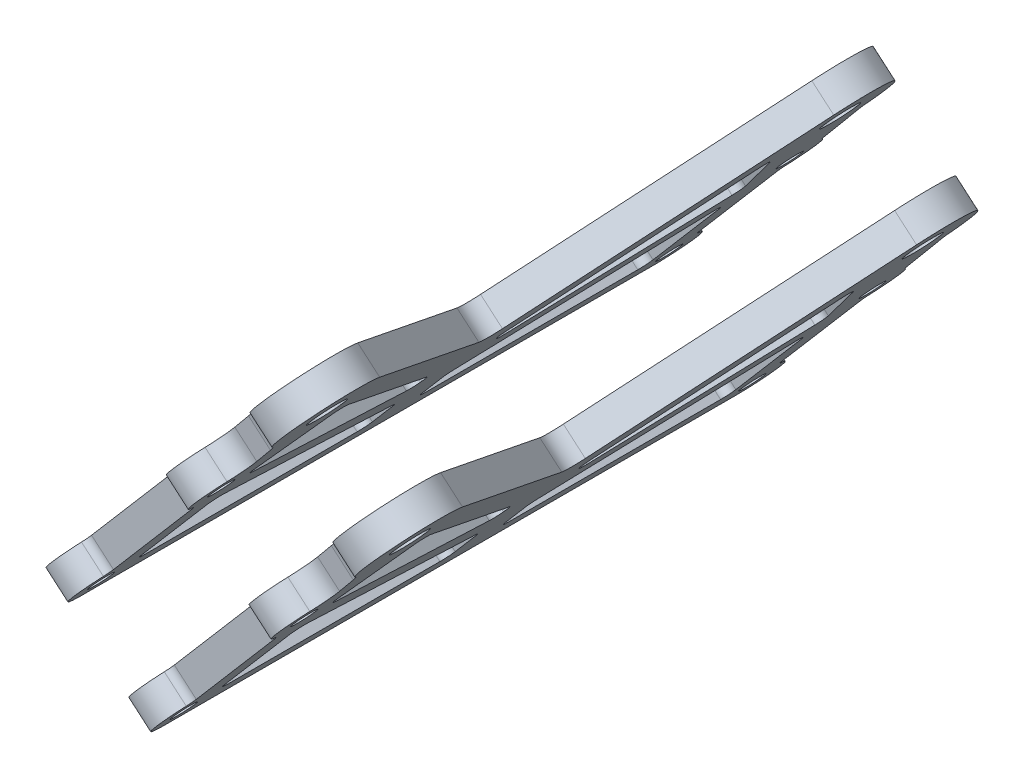
SolidWorks part; units mm, degrees
material "7075-T6, Plate (SS)"
ref_plane "Ground Plane" through (0, 0, 0) normal (0, 0, 1) x (1, 0, 0)
ref_plane "Side Plane" through (0, 0, 0) normal (0, 1, 0) x (1, 0, 0)
ref_plane "Rear Axle Centerline" through (0, 0, 0) normal (1, 0, 0) x (0, 0, -1)
sketch "Chassis Side View" plane through (0, 0, 0) normal (0, 1, 0) x (1, 0, 0)
  line L0 (0, -381) -> (2300, -381) construction
  line L1 (1150, -381) -> (1150, -856.742)
  line L2 (2150, -381) -> (2150, -1062.9307) construction
  line L3 (-753.0356, 0) -> (753.0356, 0) construction
  line L4 (2450, -381) -> (2450, -1062.9307) construction
  dimension "D1" = 2300
  dimension "D2" = 475.742
  dimension "D3" = 1150
  dimension "D4" = 381
  dimension "D5" = 150
  dimension "D6" = 150
ref_plane "Front Axle Centerline" through (2300, 0, 0) normal (1, 0, 0) x (0, 0, -1)
sketch "Front Wheel Assy Constraints" plane through (2300, 0, 0) normal (1, 0, 0) x (0, 0, -1)
  line L0 (0, 727.5) -> (0, 822.5)
  line L1 (0, 822.5) -> (-271.78, 822.5)
  line L2 (-271.78, 822.5) -> (-551.18, 822.5)
  line L3 (-551.18, 822.5) -> (-551.18, 727.5)
  line L4 (-551.18, 775) -> (0, 775) construction
  line L5 (-271.78, 822.5) -> (-271.78, 775) construction
  line L6 (-551.18, 727.5) -> (-445.4516, 727.5)
  line L7 (-445.4516, 727.5) -> (-445.4516, 798.5)
  line L8 (-445.4516, 798.5) -> (-105.7284, 798.5)
  line L9 (-105.7284, 798.5) -> (-105.7284, 727.5)
  line L10 (-105.7284, 727.5) -> (0, 727.5)
  line L11 (0, 0) -> (-673.9047, 0) construction
  line L13 (0, 753.0356) -> (0, -753.0356) construction
  dimension "D1" = 95
  dimension "D2" = 279.4
  dimension "D3" = 271.78
  dimension "D4" = 23.5
  dimension "D5" = 1550
sketch "Front Sus Front View" plane through (2300, 0, 0) normal (1, 0, 0) x (0, 0, -1)
  line L0 (0, 775) -> (0, 768.65) construction
  line L1 (0, 753.0356) -> (0, -753.0356) construction
  line L2 (0, 768.65) -> (-762, 634.2888) construction
  line L3 (0, 768.65) -> (-745.3671, 768.65) construction
  line L4 (-366.7919, -1090.2477) -> (-525.9451, 520.8571) construction
  line L5 (-366.7919, -1090.2477) -> (-379.5678, 520.8571) construction
  line L6 (-366.7919, -1090.2477) -> (0, 775) construction
  line L7 (-525.9451, 520.8571) -> (-541, 673.2571)
  line L8 (-379.5678, 520.8571) -> (-381, 701.4694)
  line L9 (0, 0) -> (-152.4, 0) construction
  line L13 (-525.9451, 520.8571) -> (-379.5678, 520.8571) construction
  dimension "D1" = 6.35
  dimension "D2" = 10
  dimension "D3" = 152.4
  dimension "D4" = 1865.2477
  dimension "D6" = 381
  dimension "D7" = 541
  dimension "D8" = 153.1418
  dimension "D5" = 152.4
ref_plane "Fron Wheel Side View Plane" through (0, 775, 0) normal (0, 1, 0) x (1, 0, 0)
sketch "Front SVSA" plane through (0, 775, 0) normal (0, 1, 0) x (1, 0, 0)
  line L0 (2271.684, -676.7175) -> (2328.316, 133.1575)
  line L1 (2300, 0) -> (2300, -771.0839) construction
  line L2 (2300, 0) -> (-2450.054, -116.0888) construction
  line L3 (-2450.054, -116.0888) -> (2298.2335, -297.0415) construction
  line L4 (-753.0356, 0) -> (753.0356, 0) construction
  point P5 (2300, -271.78)
  dimension "D1" = 4
  dimension "D2" = 1.4
  dimension "D3" = 4750.054
sketch3d "Front Chassis Side Axes"
  line L0 (2300, 520.8571, 379.5678) -> (2300, 701.4694, 381) construction
  line L1 (2300, 520.8571, 525.9451) -> (2300, 673.2571, 541) construction
  line L2 (2300, 520.8571, 379.5678) -> (2300, 701.4694, 381) construction
  line L3 (2300, 520.8571, 525.9451) -> (2300, 673.2571, 541) construction
  line L4 (2300, 673.2571, 541) -> (2300, 775, 551.0507) construction
  line L5 (2300, 701.4694, 381) -> (2300, 775, 381.5831) construction
  line L6 (2300, 775, 0) -> (2300, 775, 771.0839) construction
  line L7 (-2450.054, 775, 116.0888) -> (2349.7917, 775, 555.6101) construction
  line L8 (-2450.054, 775, 116.0888) -> (2349.9221, 775, 384.3734) construction
  line L9 (2349.9221, 775, 384.3734) -> (2177.377, 520.8571, 372.714) construction
  line L10 (2349.7917, 775, 555.6101) -> (2225.4174, 520.8571, 519.1156) construction
  line L11 (2300, 520.8571, 525.9451) -> (2300, 520.8571, 519.1156) construction
  line L12 (2300, 520.8571, 519.1156) -> (2225.4174, 520.8571, 519.1156) construction
  line L13 (2598.7501, 520.8571, 553.3017) -> (1702.4998, 520.8571, 471.2321)
  line L14 (2300, 520.8571, 379.5678) -> (2300, 520.8571, 372.714) construction
  line L15 (2300, 520.8571, 372.714) -> (2177.377, 520.8571, 372.714) construction
  line L16 (2599.5325, 520.8571, 396.3095) -> (1700.935, 520.8571, 346.0843)
  dimension "D1" = 50
  dimension "D2" = 50
  dimension "D3" = 600
  dimension "D4" = 300
  dimension "D5" = 600
  dimension "D6" = 300
sketch3d "Front Left Control Arm"
  line L0 (2300, 520.8571, 379.5678) -> (2300, 701.4694, 381) construction
  line L2 (2300, 520.8571, 379.5678) -> (2300, 701.4694, 381) construction
  line L3 (2300, 520.8571, 525.9451) -> (2300, 673.2571, 541) construction
  line L4 (2598.7501, 520.8571, 553.3017) -> (1702.4998, 520.8571, 471.2321) construction
  line L5 (2599.5325, 520.8571, 396.3095) -> (1700.935, 520.8571, 346.0843) construction
  line L6 (2598.7501, 520.8571, 553.3017) -> (1702.4998, 520.8571, 471.2321) construction
  line L7 (2599.5325, 520.8571, 396.3095) -> (1700.935, 520.8571, 346.0843) construction
  line L8 (2450, 520.8571, 539.6806) -> (2280.5957, 673.2571, 539.2232)
  line L9 (2280.5957, 673.2571, 539.2232) -> (2150, 520.8571, 512.2097)
  line L10 (2300, 520.8571, 525.9451) -> (2300, 673.2571, 541) construction
  line L11 (2300, 673.2571, 541) -> (2280.5957, 673.2571, 539.2232) construction
  line L12 (2271.684, 775, 676.7175) -> (2328.316, 775, -133.1575) construction
  line L13 (2150, 0, 512.2097) -> (2150, 520.8571, 512.2097) construction
  line L14 (2292.3517, 701.4694, 380.5725) -> (2292.3517, 775, 381.1556) construction
  line L15 (2150, 0, 381) -> (2150, 0, 1062.9307) construction
  line L16 (2450, 0, 539.6806) -> (2450, 520.8571, 539.6806) construction
  line L17 (2450, 0, 381) -> (2450, 0, 1062.9307) construction
  line L18 (2450, 520.8571, 387.9517) -> (2292.3517, 701.4694, 380.5725)
  line L19 (2292.3517, 701.4694, 380.5725) -> (2150, 520.8571, 371.1838)
  line L20 (2300, 701.4694, 381) -> (2292.3517, 701.4694, 380.5725) construction
  line L21 (2450, 0, 387.9517) -> (2450, 520.8571, 387.9517) construction
  line L22 (2150, 0, 371.1838) -> (2150, 520.8571, 371.1838) construction
  line L23 (2280.5957, 673.2571, 539.2232) -> (2280.5957, 775, 549.2738) construction
sketch3d "Front Control Arm"
  line L0 (2450, 520.8571, 387.9517) -> (2292.3517, 701.4694, 380.5725) construction
  line L1 (2292.3517, 701.4694, 380.5725) -> (2150, 520.8571, 371.1838) construction
  line L2 (2280.5957, 673.2571, 539.2232) -> (2150, 520.8571, 512.2097) construction
  line L3 (2450, 520.8571, 539.6806) -> (2280.5957, 673.2571, 539.2232) construction
  line L4 (2450, 520.8571, 387.9517) -> (2292.3517, 701.4694, 380.5725)
  line L5 (2292.3517, 701.4694, 380.5725) -> (2150, 520.8571, 371.1838)
  line L6 (2280.5957, 673.2571, 539.2232) -> (2150, 520.8571, 512.2097)
  line L7 (2450, 520.8571, 539.6806) -> (2280.5957, 673.2571, 539.2232)
  line L8 (2450, -520.8571, 539.6806) -> (2280.5957, -673.2571, 539.2232)
  line L9 (2280.5957, -673.2571, 539.2232) -> (2150, -520.8571, 512.2097)
  line L10 (2292.3517, -701.4694, 380.5725) -> (2150, -520.8571, 371.1838)
  line L11 (2450, -520.8571, 387.9517) -> (2292.3517, -701.4694, 380.5725)
ref_plane "Max Droop Plane" through (0, 0, -25.4) normal (0, 0, 1) x (1, 0, 0)
sketch3d "Shock"
  line L0 (2292.3517, 701.4694, 380.5725) -> (2293.5626, 664.4705, 414.2387) construction
  line L1 (2300, 520.8571, 525.9451) -> (2298.2629, 520.8571, 544.9158) construction
  line L2 (2150, 520.8571, 512.2097) -> (2450, 520.8571, 539.6806) construction
  line L3 (2300, 520.8571, 525.9451) -> (2300, 230.5152, 525.9451) construction
  line L4 (2293.5626, 664.4705, 414.2387) -> (2298.2629, 520.8571, 544.9158)
  dimension "D1" = 50.038
  dimension "D2" = 19.05
sketch3d "Parametric Analysis"
  line L2 (2300, 822.5, 0) -> (2300, 822.5, 271.78) construction
  line L3 (2300.4137, 822.5, 271.7939) -> (2300.4137, 822.5, -88.8537) construction
  line L4 (2450, 520.8571, 387.9517) -> (2292.3526, 701.4695, 380.5568)
  line L5 (2292.3526, 701.4695, 380.5568) -> (2150, 520.8571, 371.1838)
  line L6 (2450, 520.8571, 539.6806) -> (2280.5972, 673.2586, 539.2077)
  line L7 (2280.5972, 673.2586, 539.2077) -> (2150, 520.8571, 512.2097)
  line L8 (2292.3517, 701.4694, 380.5725) -> (2300, 822.5, 271.78) construction
  line L9 (2450, 520.8571, 387.9517) -> (2292.3517, 701.4694, 380.5725) construction
  line L10 (2292.3517, 701.4694, 380.5725) -> (2150, 520.8571, 371.1838) construction
  line L11 (2450, 520.8571, 539.6806) -> (2280.5957, 673.2571, 539.2232) construction
  line L12 (2280.5957, 673.2571, 539.2232) -> (2150, 520.8571, 512.2097) construction
  line L13 (2280.5957, 673.2571, 539.2232) -> (2292.3517, 701.4694, 380.5725) construction
  line L14 (2300, 822.5, 271.78) -> (2280.5957, 673.2571, 539.2232) construction
  line L15 (2300, 822.5, 271.78) -> (2300.4132, 720.8156, 271.78) construction
  line L16 (2280.5972, 673.2586, 539.2077) -> (2300.4137, 822.5, 271.7939) construction
  line L17 (2300.4137, 822.5, 271.7939) -> (2292.3526, 701.4695, 380.5568) construction
  line L18 (2280.5972, 673.2586, 539.2077) -> (2292.3526, 701.4695, 380.5568) construction
  line L19 (2300.4137, 822.5, 271.7939) -> (2300.4137, 720.8148, 271.7641) construction
  line L23 (2292.3517, 701.4694, 380.5725) -> (2265.8007, 667.7821, 378.8214) construction
  line L30 (2265.8007, 667.7821, 378.8214) -> (2325.2406, 663.7898, 382.112) construction
  line L31 (2325.2406, 663.7898, 382.112) -> (2293.5626, 664.4705, 414.2387) construction
  line L32 (2292.3517, 701.4694, 380.5725) -> (2325.2406, 663.7898, 382.112) construction
  line L33 (2293.5626, 664.4705, 414.2387) -> (2265.8007, 667.7821, 378.8214) construction
  line L34 (2292.3526, 701.4695, 380.5568) -> (2293.5633, 664.4722, 414.2247) construction
  line L35 (2292.3517, 701.4694, 380.5725) -> (2293.5626, 664.4705, 414.2387) construction
  line L39 (2300.4137, 822.5, 271.7939) -> (2300.4137, 822.5798, 0.014)
  line L40 (2300.4137, 822.5798, 0.014) -> (2300.4137, 727.5798, -0.014)
  line L41 (2300, 727.5, 0) -> (2300, 822.5, 0) construction
  line L42 (2298.2629, 520.8571, 544.9158) -> (2293.5633, 664.4722, 414.2247)
  point P5 (2300.4137, 775.0798, 0)
  dimension "D1" = 25.4
  dimension "D2" = 194.2357
  dimension "D3" = 0.0798
  dimension "D4" = 0.017
sketch3d "3DSketch1"
  line L0 (2293.5626, 664.4705, 414.2387) -> (2298.2629, 520.8571, 544.9158) construction
  line L1 (2280.5972, 673.2586, 539.2077) -> (2150, 520.8571, 512.2097) construction
  line L2 (2450, 520.8571, 539.6806) -> (2280.5972, 673.2586, 539.2077) construction
  line L3 (2292.3526, 701.4695, 380.5568) -> (2150, 520.8571, 371.1838) construction
  line L4 (2450, 520.8571, 387.9517) -> (2292.3526, 701.4695, 380.5568) construction
  line L5 (2293.5626, 664.4705, 414.2387) -> (2298.2629, 520.8571, 544.9158)
  line L6 (2280.5972, 673.2586, 539.2077) -> (2150, 520.8571, 512.2097)
  line L7 (2450, 520.8571, 539.6806) -> (2280.5972, 673.2586, 539.2077)
  line L8 (2292.3526, 701.4695, 380.5568) -> (2150, 520.8571, 371.1838)
  line L9 (2450, 520.8571, 387.9517) -> (2292.3526, 701.4695, 380.5568)
  line L10 (2450, 520.8571, 539.6806) -> (2450, 470.0571, 539.6806) construction
  line L11 (2150, 520.8571, 512.2097) -> (2150, 470.0571, 512.2097) construction
  line L12 (2298.2629, 520.8571, 544.9158) -> (2298.2629, 470.0571, 544.9158) construction
  line L13 (2450, 520.8571, 387.9517) -> (2450, 470.0571, 387.9517) construction
  line L14 (2150, 520.8571, 371.1838) -> (2150, 470.0571, 371.1838) construction
  line L15 (2150, -520.8571, 512.2097) -> (2150, -470.0571, 512.2097) construction
  line L16 (2298.2629, -520.8571, 544.9158) -> (2298.2629, -470.0571, 544.9158) construction
  line L17 (2450, -520.8571, 539.6806) -> (2450, -470.0571, 539.6806) construction
  line L18 (2293.5626, -664.4705, 414.2387) -> (2298.2629, -520.8571, 544.9158)
  line L19 (2280.5972, -673.2586, 539.2077) -> (2150, -520.8571, 512.2097)
  line L20 (2450, -520.8571, 539.6806) -> (2280.5972, -673.2586, 539.2077)
  line L21 (2450, -520.8571, 387.9517) -> (2450, -470.0571, 387.9517) construction
  line L22 (2150, -520.8571, 371.1838) -> (2150, -470.0571, 371.1838) construction
  line L23 (2292.3526, -701.4695, 380.5568) -> (2150, -520.8571, 371.1838)
  line L24 (2450, -520.8571, 387.9517) -> (2292.3526, -701.4695, 380.5568)
  line L25 (2280.5972, 673.2586, 539.2077) -> (2280.5972, 673.2586, 216.3834) construction
  line L26 (2450, 520.8571, 539.6806) -> (2457.3728, 529.0523, 539.6794) construction
  line L27 (2300, 775, 551.18) -> (2300, 775, 0) construction
  line L29 (2457.3728, 529.0523, 539.6794) -> (2420.3829, 562.3299, 539.5762) construction
  dimension "D1" = 50.8
  dimension "D2" = 304.9478
  dimension "D3" = 544.9185
  dimension "D4" = 11.0236
ref_plane "Plane1" through (0, 718.612, 0) normal (0, 1, 0) x (1, 0, 0)
ref_plane "Plane2" through (982.32, -841.7776, 0) normal (-0.7593, 0.6507, 0) x (-0.6449, -0.7526, -0.1333)
sketch "Sketch1" plane through (982.32, -841.7776, 0) normal (-0.7593, 0.6507, 0) x (-0.6449, -0.7526, -0.1333)
  line L0 (-1846.7729, 268.4004) -> (-1827.9718, 128.6334) construction
  line L1 (-1846.7729, 268.4004) -> (-1849.6512, 289.7977) construction
  line L2 (-1837.3723, 198.5169) -> (-1809.8881, 202.214) construction
  line L3 (-1846.7729, 268.4004) -> (-1808.5429, 273.543) construction
  line L4 (-1825.0935, 107.2362) -> (-1849.3765, 125.8105)
  line L5 (-1849.6512, 289.7977) -> (-1868.1701, 265.5221)
  line L6 (-1849.6512, 289.7977) -> (-1748.9581, 303.3427)
  line L7 (-1825.0935, 107.2362) -> (-1724.4004, 120.7811)
  line L8 (-1827.9718, 128.6334) -> (-1825.0935, 107.2362) construction
  line L9 (-1748.9581, 303.3427) -> (-1724.4004, 120.7811)
  line L10 (-1868.1701, 265.5221) -> (-1849.3765, 125.8105)
  line L11 (-1764.717, 287.127) -> (-1815.0635, 280.3545) construction
  circle A0 centre (-1846.7729, 268.4004) radius 4.7625
  circle A1 centre (-1827.9718, 128.6334) radius 4.7625
  circle A2 centre (-1764.717, 287.127) radius 3.175
  circle A4 centre (-1815.0635, 280.3545) radius 3.175
  circle A5 centre (-1743.8841, 132.256) radius 3.175
  circle A6 centre (-1794.2307, 125.4835) radius 3.175
  circle A7 centre (-1779.4738, 206.3053) radius 3.175
  point P6 (-1837.3723, 198.5169)
  dimension "D1" = 9.525
  dimension "D2" = 9.525
  dimension "D11" = 6.35
  dimension "D15" = 6.35
  dimension "D16" = 6.35
  dimension "D3" = 21.59
  dimension "D4" = 21.59
  dimension "D5" = 21.59
  dimension "D6" = 101.6
  dimension "D7" = 101.6
  dimension "D8" = 21.59
  dimension "D9" = 140.97
  dimension "D10" = 30.5329
  dimension "D12" = 13.97
  dimension "D13" = 17.78
  dimension "D14" = 50.8
  dimension "D17" = 43.18
  dimension "D18" = 92.1029
extrude "Boss-Extrude1" add sketch "Sketch1" along normal blind 18.9611 and the other way blind 18.9611
ref_plane "Cutting Plane" through (967.9221, -829.4397, 0) normal (-0.7593, 0.6507, 0) x (0, 0, 1)
sketch "Sketch4" plane through (967.9221, -829.4397, 0) normal (-0.7593, 0.6507, 0) x (0, 0, 1)
  line L0 (512.2097, 1794.5055) -> (441.6967, 1736.0855) construction
  line L1 (441.6967, 1736.0855) -> (519.8297, 1710.6855) construction
  line L2 (519.8297, 1761.4855) -> (441.6967, 1736.0855) construction
  line L3 (441.6967, 1736.0855) -> (363.5638, 1761.4855) construction
  line L4 (441.6967, 1736.0855) -> (363.5638, 1710.6855) construction
  line L6 (363.5638, 1761.4855) -> (371.1838, 1794.5055) construction
  line L7 (519.8297, 1761.4855) -> (522.1855, 1754.2388) construction
  line L8 (522.1855, 1752.5829) -> (522.1855, 1719.5881)
  line L9 (512.2097, 1794.5055) -> (519.8297, 1761.4855) construction
  line L10 (512.2097, 1794.5055) -> (520.3121, 1784.7259) construction
  line L12 (361.208, 1752.5829) -> (361.208, 1719.5881)
  line L13 (363.5638, 1703.0655) -> (519.8297, 1703.0655)
  line L15 (363.5638, 1761.4855) -> (361.208, 1754.2388) construction
  line L16 (520.0113, 1782.5593) -> (518.9924, 1775.2208)
  line L20 (371.1838, 1794.5055) -> (441.6967, 1736.0855) construction
  line L21 (371.1838, 1794.5055) -> (379.2863, 1804.2851) construction
  line L23 (441.6967, 1769.1055) -> (441.6967, 1703.0655) construction
  line L28 (379.2863, 1804.2851) -> (438.4558, 1755.2631)
  line L30 (504.1072, 1804.2851) -> (444.9377, 1755.2631)
  line L36 (381.7632, 1781.226) -> (375.0049, 1760.437)
  line L37 (376.6352, 1757.2362) -> (428.2621, 1740.4529)
  line L38 (431.0033, 1741.248) -> (431.1991, 1741.4843)
  line L39 (430.8636, 1745.0608) -> (385.7992, 1782.3967)
  line L40 (503.5863, 1782.8465) -> (510.634, 1761.167)
  line L41 (509.0037, 1757.9661) -> (455.2625, 1740.4956)
  line L42 (452.202, 1741.782) -> (452.0386, 1742.1112)
  line L43 (452.6934, 1745.1963) -> (499.5502, 1784.0171)
  line L44 (533.7997, 1794.5055) -> (512.2097, 1816.0955)
  line L45 (512.2097, 1816.0955) -> (371.2397, 1816.0954)
  line L46 (371.2397, 1816.0954) -> (349.5938, 1794.5055)
  line L47 (349.5938, 1794.5055) -> (349.5938, 1692.9055)
  line L48 (349.5938, 1692.9055) -> (533.7997, 1692.9055)
  line L49 (533.7997, 1692.9055) -> (533.7997, 1794.5055)
  line L50 (360.5084, 1786.6541) -> (358.7544, 1768.2714)
  line L51 (379.2863, 1804.2851) -> (360.1806, 1788.1637) construction
  arc A0 (523.5016, 1754.8085) -> (522.8037, 1768.5012) centre (519.8297, 1761.4855) ccw
  arc A2 (521.6038, 1785.9592) -> (504.1072, 1804.2851) centre (512.2097, 1794.5055) ccw
  arc A4 (359.8919, 1754.8085) -> (358.0604, 1766.7559) centre (363.5638, 1761.4855) cw
  arc A5 (520.0113, 1782.5593) -> (521.6038, 1785.9592) centre (526.3009, 1781.6861) cw
  arc A6 (522.8037, 1768.5012) -> (518.9924, 1775.2208) centre (525.2821, 1774.3476) cw
  arc A7 (379.2863, 1804.2851) -> (360.1806, 1788.1637) centre (371.1838, 1794.5055) ccw
  arc A10 (428.2621, 1740.4529) -> (431.0033, 1741.248) centre (429.0474, 1742.8685) ccw
  arc A11 (431.1991, 1741.4843) -> (430.8636, 1745.0608) centre (429.2432, 1743.1048) ccw
  arc A12 (375.0049, 1760.437) -> (376.6352, 1757.2362) centre (377.4205, 1759.6517) ccw
  arc A13 (381.7632, 1781.226) -> (385.7992, 1782.3967) centre (384.1787, 1780.4407) cw
  arc A14 (452.6934, 1745.1963) -> (452.0386, 1742.1112) centre (454.3139, 1743.2403) ccw
  arc A15 (452.202, 1741.782) -> (455.2625, 1740.4956) centre (454.4773, 1742.9111) ccw
  arc A16 (509.0037, 1757.9661) -> (510.634, 1761.167) centre (508.2184, 1760.3817) ccw
  arc A17 (503.5863, 1782.8465) -> (499.5502, 1784.0171) centre (501.1707, 1782.0612) ccw
  arc A20 (444.9377, 1755.2631) -> (438.4558, 1755.2631) centre (441.6967, 1759.175) cw
  arc A22 (358.0604, 1766.7559) -> (358.7544, 1768.2714) centre (356.2259, 1768.5127) ccw
  arc A23 (360.5084, 1786.6541) -> (360.1806, 1788.1637) centre (357.9799, 1786.8954) ccw
  circle A24 centre (363.5638, 1710.6855) radius 7.62 construction
  circle A25 centre (519.8297, 1710.6855) radius 7.62 construction
  arc A26 (359.8919, 1717.3625) -> (363.5638, 1703.0655) centre (363.5638, 1710.6855) ccw
  arc A27 (519.8297, 1703.0655) -> (523.5016, 1717.3625) centre (519.8297, 1710.6855) ccw
  arc A28 (523.5016, 1754.8085) -> (522.1855, 1752.5829) centre (524.7255, 1752.5829) ccw
  arc A29 (523.5016, 1717.3625) -> (522.1855, 1719.5881) centre (524.7255, 1719.5881) cw
  arc A30 (359.8919, 1717.3625) -> (361.208, 1719.5881) centre (358.668, 1719.5881) ccw
  arc A31 (359.8919, 1754.8085) -> (361.208, 1752.5829) centre (358.668, 1752.5829) cw
  point P19 (519.8297, 1710.6855)
  point P28 (441.6967, 1736.0855)
  point P36 (518.1163, 1768.9104)
  point P41 (358.6638, 1767.3211)
  point P46 (441.6967, 1736.0855)
  point P50 (360.5893, 1787.5022)
  point P56 (429.9027, 1739.9196)
  point P59 (432.8196, 1743.4403)
  point P62 (374.2197, 1758.0214)
  point P65 (382.9194, 1784.7826)
  point P73 (451.1445, 1743.913)
  point P76 (453.1769, 1739.8176)
  point P79 (511.4193, 1758.7514)
  point P82 (502.43, 1786.4031)
  point P91 (441.6967, 1752.578)
  point P93 (522.1855, 1717.9322)
  point P107 (361.208, 1717.9322)
  dimension "D1" = 7.62
  dimension "D4" = 15.24
  dimension "D3" = 12.7
  dimension "D6" = 2.54
  dimension "D7" = 7.62
  dimension "D10" = 6.35
  dimension "D11" = 6.35
  dimension "D12" = 12.7
  dimension "D13" = 20.2727
  dimension "D14" = 2.54
  dimension "D15" = 24.9985
  dimension "D18" = 2.54
  dimension "D22" = 2.54
  dimension "D24" = 5.08
  dimension "D5" = 15.24
  dimension "D16" = 15.24
  dimension "D17" = 4.572
  dimension "D19" = 12.7
  dimension "D20" = 4.572
extrude "Cut-Extrude1" cut sketch "Sketch4" against normal through all
ref_plane "Middle Cut Plane" through (585.1344, 682.8279, -745.0227) normal (0.5011, 0.5847, -0.638) x (-0.8654, 0.3386, -0.3694)
sketch "Sketch5" plane through (585.1344, 682.8279, -745.0227) normal (0.5011, 0.5847, -0.638) x (-0.8654, 0.3386, -0.3694)
  line L0 (-1873.4939, 730.0626) -> (-1855.9043, 697.889) construction
  line L1 (-1891.484, 739.9887) -> (-1872.1391, 750.5648)
  line L2 (-1891.484, 739.9887) -> (-1795.3035, 564.0621)
  line L3 (-1795.3035, 564.0621) -> (-1775.9586, 574.6381)
  line L4 (-1775.9586, 574.6381) -> (-1872.1391, 750.5648)
  point P6 (-1881.8115, 745.2767)
  point P7 (-1881.8115, 745.2767)
  dimension "D1" = 11.0236
extrude "Cut-Extrude2" cut sketch "Sketch5" against normal through all
sketch "Sketch6" plane through (967.9221, -829.4397, 0) normal (-0.7593, 0.6507, 0) x (0, 0, 1)
  line L0 (371.368, 1743.4331) -> (371.368, 1715.7655)
  line L1 (373.908, 1713.2255) -> (432.328, 1713.2255)
  line L2 (434.868, 1715.7655) -> (434.868, 1724.4415)
  line L3 (433.1133, 1726.8571) -> (374.6933, 1745.8487)
  line L4 (448.5255, 1724.4415) -> (448.5255, 1715.7655)
  line L5 (451.0655, 1713.2255) -> (509.4855, 1713.2255)
  line L6 (512.0255, 1715.7655) -> (512.0255, 1743.4331)
  line L7 (508.7002, 1745.8487) -> (450.2802, 1726.8571)
  line L8 (509.0037, 1757.9661) -> (455.2625, 1740.4956) construction
  line L9 (522.1855, 1752.5829) -> (522.1855, 1719.5881) construction
  line L10 (363.5638, 1703.0655) -> (519.8297, 1703.0655) construction
  line L11 (361.208, 1752.5829) -> (361.208, 1719.5881) construction
  line L12 (376.6352, 1757.2362) -> (428.2621, 1740.4529) construction
  arc A0 (509.4855, 1713.2255) -> (512.0255, 1715.7655) centre (509.4855, 1715.7655) ccw
  arc A1 (512.0255, 1743.4331) -> (508.7002, 1745.8487) centre (509.4855, 1743.4331) ccw
  arc A2 (450.2802, 1726.8571) -> (448.5255, 1724.4415) centre (451.0655, 1724.4415) ccw
  arc A3 (451.0655, 1713.2255) -> (448.5255, 1715.7655) centre (451.0655, 1715.7655) cw
  arc A4 (433.1133, 1726.8571) -> (434.868, 1724.4415) centre (432.328, 1724.4415) cw
  arc A5 (434.868, 1715.7655) -> (432.328, 1713.2255) centre (432.328, 1715.7655) cw
  arc A6 (373.908, 1713.2255) -> (371.368, 1715.7655) centre (373.908, 1715.7655) cw
  arc A7 (371.368, 1743.4331) -> (374.6933, 1745.8487) centre (373.908, 1743.4331) cw
  point P20 (512.0255, 1713.2255)
  point P27 (448.5255, 1713.2255)
  point P32 (434.868, 1713.2255)
  point P35 (371.368, 1713.2255)
  dimension "D9" = 2.54
  dimension "D1" = 10.16
  dimension "D2" = 10.16
  dimension "D3" = 63.5
  dimension "D4" = 63.5
  dimension "D5" = 10.16
  dimension "D6" = 11.43
  dimension "D7" = 11.43
  dimension "D8" = 10.16
extrude "Cut-Extrude3" cut sketch "Sketch6" against normal through all both and the other way through all
sketch "Sketch7" plane through (967.9221, -829.4397, 0) normal (-0.7593, 0.6507, 0) x (0, 0, 1)
  circle A0 centre (441.6967, 1736.0855) radius 3.175
  dimension "D1" = 6.35
sketch "Sketch8" plane through (996.7178, -854.1156, 0) normal (0.7593, -0.6507, 0) x (0, 0, -1)
  circle A0 centre (-441.6967, 1736.0855) radius 3.175
  dimension "D1" = 6.35
extrude "Boss-Extrude2" add sketch "Sketch7" against normal up to surface (7.9375 mm away) up to face at (2096.2919, 475.1232, 480.1071)
extrude "Boss-Extrude3" add sketch "Sketch8" against normal up to surface (7.9375 mm away) contours A0 up to face at (2113.0332, 460.7771, 480.1071)
equation "\"wheelbase\"= 2.3m"
equation "\"track_front_outer\"= 1.55m"
equation "\"cg_h\"= 18.73in"
equation "\"cg_b\"= \"wheelbase\" / 2"
equation "\"chassis_ride_height\"= 15in"
equation "\"hub_offset\"= 23.5mm"
equation "\"tire_radius\"= 11in"
equation "\"tire_radius_loaded\"= 10.7in"
equation "\"tire_width\"= 95mm"
equation "\"static_camber\"= 0deg"
equation "\"caster_static\"= 4deg"
equation "\"control_arm_ratio\"= 0.95"
equation "\"roll_center_height\"= 6in"
equation "\"scrub_radius\"= 0.25in"
equation "\"camber_change_rate\"= 0.5deg'per inch of travel"
equation "\"fvsa_length\"= atn ( 1 / \"camber_change_rate\" )"
equation "\"svsa_length\"= 2.5 * \"wheelbase\""
equation "\"svsa_height\"= 1"
equation "\"anti_squat_rear\"= 0.15"
equation "\"front_brakes\"= .75"
equation "\"anti_dive_front\"= 0.1"
equation "\"D1@Chassis Side View\" = \"wheelbase\""
equation "\"D2@Chassis Side View\" = \"cg_h\""
equation "\"D3@Chassis Side View\" = \"cg_b\""
equation "\"D4@Chassis Side View\" = \"chassis_ride_height\""
equation "\"D1@Front Axle Centerline\"=\"wheelbase\""
equation "\"D1@Front Wheel Assy Constraints\" = \"tire_width\""
equation "\"D2@Front Wheel Assy Constraints\" = \"tire_radius\""
equation "\"D3@Front Wheel Assy Constraints\" = \"tire_radius_loaded\""
equation "\"D4@Front Wheel Assy Constraints\" = \"hub_offset\""
equation "\"D1@Front Sus Front View\" = \"scrub_radius\""
equation "\"static_kingpin\"= 10deg"
equation "\"D2@Front Sus Front View\" = \"static_kingpin\""
equation "\"D3@Front Sus Front View\" = \"roll_center_height\""
equation "\"D6@Front Sus Front View\" = \"chassis_ride_height\""
equation "\"D7@Front Sus Front View\"=\"chassis_ride_height\" + 160mm"
equation "\"D1@Front SVSA\" = \"caster_static\""
equation "\"D4@Front Sus Front View\"=\"fvsa_length\"+10"
equation "\"D5@Front Wheel Assy Constraints\"=\"track_front_outer\""
equation "\"phi_front\"= atn ( \"anti_dive_front\" / \"front_brakes\" * \"cg_h\" / \"wheelbase\" )"
equation "\"anti_lift_rear\"= 0.1"
equation "\"a\"= 0"
